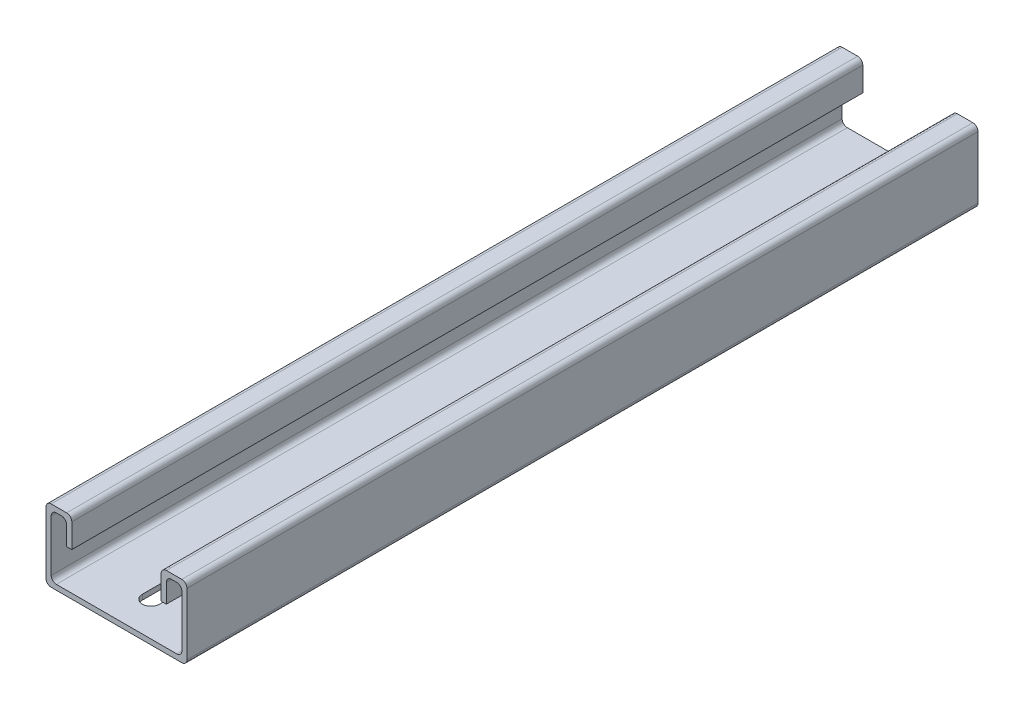
SolidWorks part; units mm, degrees
material "1345 合金"
ref_plane "前视基准面" through (0, 0, 0) normal (0, 0, 1) x (1, 0, 0)
ref_plane "上视基准面" through (0, 0, 0) normal (0, 1, 0) x (1, 0, 0)
ref_plane "右视基准面" through (0, 0, 0) normal (1, 0, 0) x (0, 0, -1)
sketch "草图1" plane through (0, 0, 0) normal (0, 0, 1) x (1, 0, 0)
  line L0 (-19, 10.5) -> (-14.5, 10.5)
  line L5 (-19, -10.5) -> (19, -10.5)
  line L6 (-20.5, -9) -> (-20.5, 9)
  line L7 (-19, 10.5) -> (19, 10.5) construction
  line L8 (20.5, -9) -> (20.5, 9)
  line L9 (-20.5, -10.5) -> (20.5, 10.5) construction
  line L10 (-20.5, 10.5) -> (20.5, -10.5) construction
  line L11 (19, 10.5) -> (14.5, 10.5)
  line L12 (13, 9) -> (13, 2)
  line L13 (-13, 9) -> (-13, 2)
  line L14 (-13, 2) -> (-14.5, 2)
  line L15 (13, 2) -> (14.5, 2)
  line L16 (-14.5, 2) -> (-14.5, 7.5)
  line L17 (-16, 9) -> (-17.5, 9)
  line L18 (-19, 7.5) -> (-19, -7.5)
  line L19 (-17.5, -9) -> (17.5, -9)
  line L20 (19, -7.5) -> (19, 7.5)
  line L21 (17.5, 9) -> (16, 9)
  line L22 (14.5, 7.5) -> (14.5, 2)
  arc A4 (19, -10.5) -> (20.5, -9) centre (19, -9) ccw
  arc A5 (19, 10.5) -> (20.5, 9) centre (19, 9) cw
  arc A6 (-20.5, 9) -> (-19, 10.5) centre (-19, 9) cw
  arc A7 (-19, -10.5) -> (-20.5, -9) centre (-19, -9) cw
  arc A8 (-14.5, 10.5) -> (-13, 9) centre (-14.5, 9) cw
  arc A9 (14.5, 10.5) -> (13, 9) centre (14.5, 9) ccw
  arc A10 (19, 7.5) -> (17.5, 9) centre (17.5, 7.5) ccw
  arc A11 (17.5, -9) -> (19, -7.5) centre (17.5, -7.5) ccw
  arc A12 (-19, -7.5) -> (-17.5, -9) centre (-17.5, -7.5) ccw
  arc A13 (-17.5, 9) -> (-19, 7.5) centre (-17.5, 7.5) ccw
  arc A14 (-14.5, 7.5) -> (-16, 9) centre (-16, 7.5) ccw
  arc A15 (16, 9) -> (14.5, 7.5) centre (16, 7.5) ccw
  point P0 (0, 0)
  point P26 (-13, 10.5)
  point P29 (13, 10.5)
  dimension "D3" = 1.5
  dimension "D5" = 1.5
  dimension "D7" = 1.5
  dimension "D12" = 1.5
  dimension "D13" = 1.5
  dimension "D14" = 1.5
  dimension "D1" = 41
  dimension "D2" = 21
  dimension "D4" = 6
  dimension "D6" = 6
  dimension "D8" = 7
  dimension "D9" = 7
  dimension "D10" = 1.5
  dimension "D11" = 1.5
extrude "凸台-拉伸1" add sketch "草图1" along normal blind 230
sketch "草图3" plane through (0, 0, 0) normal (0, 1, 0) x (1, 0, 0)
  line L1 (0, -10) -> (0, -220) construction
  line L2 (2.5, -10) -> (2.5, -220)
  line L3 (-2.5, -10) -> (-2.5, -220)
  line L4 (0, -10) -> (0, 0) construction
  arc A0 (2.5, -10) -> (-2.5, -10) centre (0, -10) ccw
  arc A1 (-2.5, -220) -> (2.5, -220) centre (0, -220) ccw
  point P5 (0, -115)
  dimension "D1" = 2.5
  dimension "D2" = 210
  dimension "D3" = 10
extrude "切除-拉伸1" cut sketch "草图3" against normal blind 100 contours L2 A1 L3 A0
